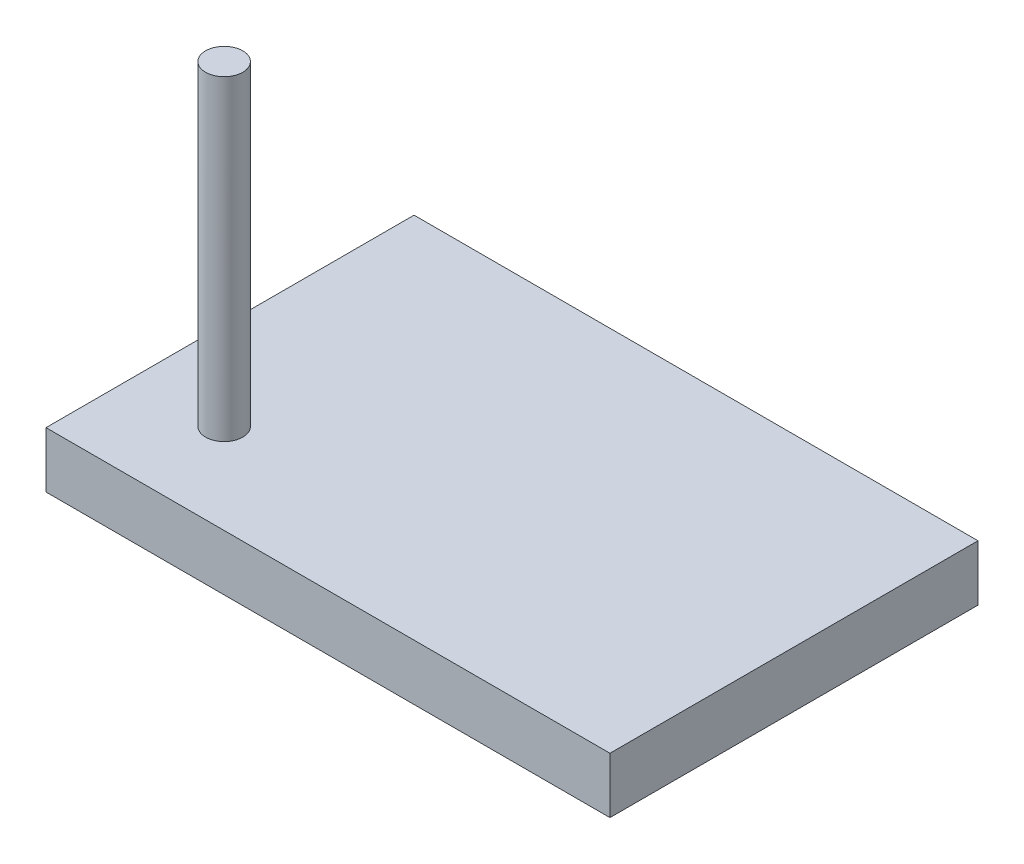
SolidWorks part; units mm, degrees
ref_plane "Front Plane" through (0, 0, 0) normal (0, 0, 1) x (1, 0, 0)
ref_plane "Top Plane" through (0, 0, 0) normal (0, 1, 0) x (1, 0, 0)
ref_plane "Right Plane" through (0, 0, 0) normal (1, 0, 0) x (0, 0, -1)
sketch "Sketch1" plane through (0, 0, 0) normal (0, 1, 0) x (1, 0, 0)
  line L1 (-75.8382, -49.4928) -> (75.8382, -49.4928)
  line L2 (-75.8382, -49.4928) -> (-75.8382, 49.4928)
  line L3 (-75.8382, 49.4928) -> (75.8382, 49.4928)
  line L4 (75.8382, -49.4928) -> (75.8382, 49.4928)
  line L5 (-75.8382, -49.4928) -> (75.8382, 49.4928) construction
  line L6 (-75.8382, 49.4928) -> (75.8382, -49.4928) construction
  point P0 (0, 0)
  dimension "D1" = 151.6765
extrude "Boss-Extrude1" add sketch "Sketch1" along normal blind 15
sketch "Sketch2" plane through (0, 15, 0) normal (0, 1, 0) x (1, 0, 0)
  circle A0 centre (-52.1539, -25.2559) radius 5
  dimension "D1" = 10
extrude "Boss-Extrude2" add sketch "Sketch2" along normal blind 85
sketch "Sketch3" plane through (0, 15, 0) normal (0, 1, 0) x (1, 0, 0)
  spline S0 degree 3 poles (-33.1116, -37.7623) (7.4392, -48.6006) (-2.2835, -4.8975) (44.4468, 45.037) (63.9722, 17.6572) knots 0 0 0 0 0.453955 1 1 1 1
